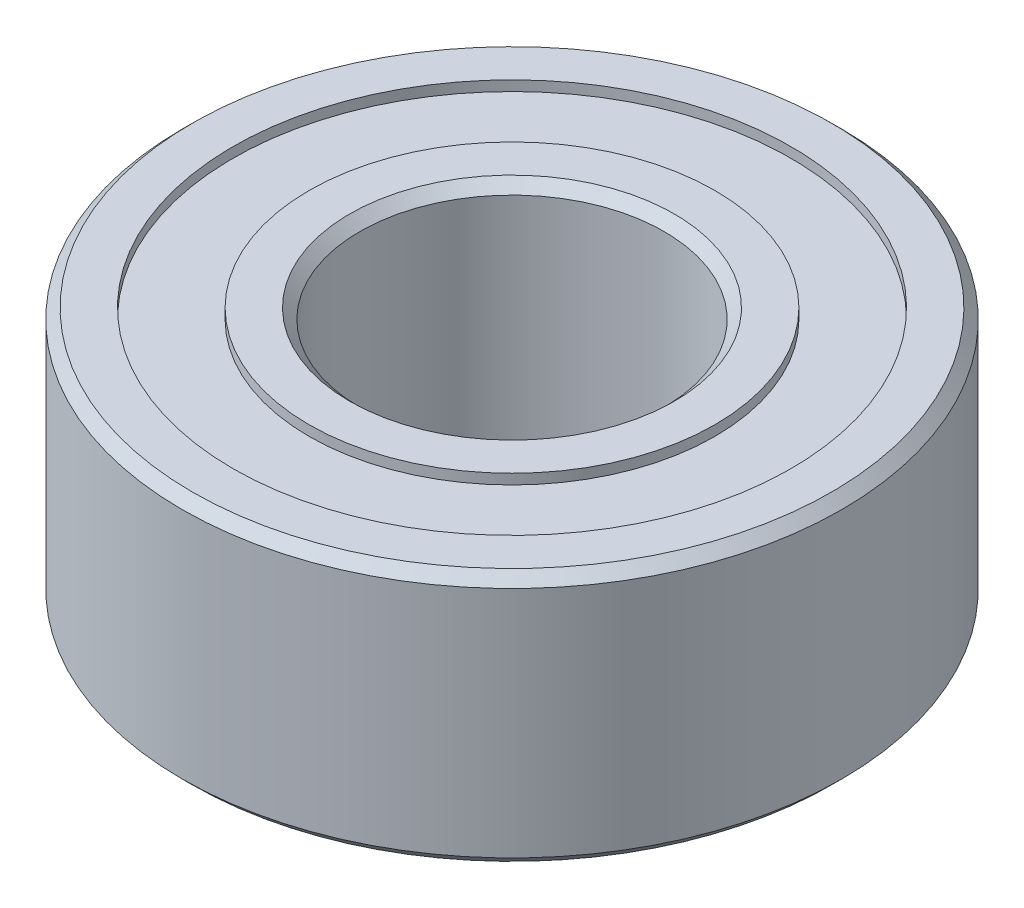
SolidWorks part; units mm, degrees
ref_plane "Front Plane" through (0, 0, 0) normal (0, 0, 1) x (1, 0, 0)
ref_plane "Top Plane" through (0, 0, 0) normal (0, 1, 0) x (1, 0, 0)
ref_plane "Right Plane" through (0, 0, 0) normal (1, 0, 0) x (0, 0, -1)
sketch "Sketch1" plane through (0, 0, 0) normal (0, 1, 0) x (1, 0, 0)
  circle A0 centre (0, 0) radius 6.5
  circle A1 centre (0, 0) radius 3
  dimension "D1" = 13
  dimension "D2" = 6
extrude "Boss-Extrude1" add sketch "Sketch1" along normal blind 5
sketch "Sketch2" plane through (0, 5, 0) normal (0, 1, 0) x (1, 0, 0)
  circle A0 centre (0, 0) radius 4
  circle A1 centre (0, 0) radius 5.5
  dimension "D1" = 11
  dimension "D2" = 8
extrude "Cut-Extrude1" cut sketch "Sketch2" against normal blind 0.2
sketch "Sketch3" plane through (0, 0, 0) normal (0, -1, 0) x (1, 0, 0)
  circle A0 centre (0, 0) radius 4 construction
  circle A1 centre (0, 0) radius 5.5
  circle A2 centre (0, 0) radius 5.5
  circle A3 centre (0, 0) radius 4
  dimension "D1" = 0
extrude "Cut-Extrude2" cut sketch "Sketch3" against normal blind 0.2
chamfer "Chamfer1" distance 0.2 angle 45 4 edges at (0, 5, 6.5) (0, 0, 6.5) (0, 5, 3) (0, 0, 3)
